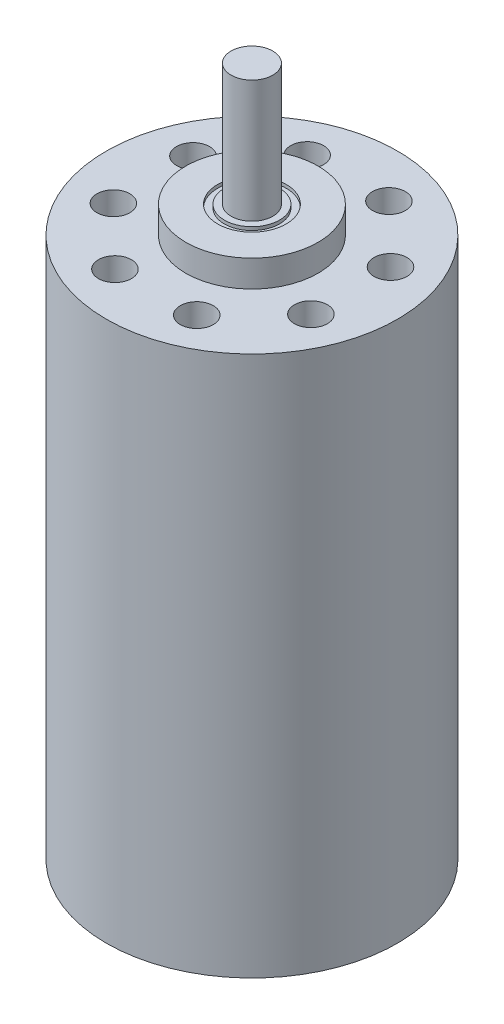
SolidWorks part; units mm, degrees
ref_plane "Front Plane" through (0, 0, 0) normal (0, 0, 1) x (1, 0, 0)
ref_plane "Top Plane" through (0, 0, 0) normal (0, 1, 0) x (1, 0, 0)
ref_plane "Right Plane" through (0, 0, 0) normal (1, 0, 0) x (0, 0, -1)
sketch "Sketch1" plane through (0, 0, 0) normal (0, 1, 0) x (1, 0, 0)
  circle A0 centre (0, 0) radius 11.049
  dimension "D1" = 22.098
extrude "Boss-Extrude1" add sketch "Sketch1" along normal blind 40.9956
sketch "Sketch2" plane through (0, 40.9956, 0) normal (0, 1, 0) x (1, 0, 0)
  circle A0 centre (0, 0) radius 5.0165
  dimension "D1" = 10.033
extrude "Boss-Extrude2" add sketch "Sketch2" along normal blind 2.032
sketch "Sketch3" plane through (0, 43.0276, 0) normal (0, 1, 0) x (1, 0, 0)
  circle A0 centre (0, 0) radius 1.585
  dimension "D1" = 3.17
extrude "Boss-Extrude3" add sketch "Sketch3" along normal blind 9.271
sketch "Sketch4" plane through (0, 52.2986, 0) normal (0, 1, 0) x (1, 0, 0)
  circle A0 centre (0, 0) radius 1.5939
  dimension "D1" = 3.1877
sketch "Sketch5" plane through (0, 40.9956, 0) normal (0, 1, 0) x (1, 0, 0)
  line L1 (-3.1626, 7.3483) -> (-7.4323, 2.9598) construction
  line L2 (-7.4323, 2.9598) -> (-7.3483, -3.1626) construction
  line L3 (-7.3483, -3.1626) -> (-2.9598, -7.4323) construction
  line L4 (-2.9598, -7.4323) -> (3.1626, -7.3483) construction
  line L5 (3.1626, -7.3483) -> (7.4323, -2.9598) construction
  line L6 (7.4323, -2.9598) -> (7.3483, 3.1626) construction
  line L7 (7.3483, 3.1626) -> (2.9598, 7.4323) construction
  line L8 (2.9598, 7.4323) -> (-3.1626, 7.3483) construction
  circle A0 centre (0, 0) radius 7.391 construction
  circle A1 centre (-7.4323, 2.9598) radius 1.25
  circle A2 centre (-3.1626, 7.3483) radius 1.25
  circle A3 centre (2.9598, 7.4323) radius 1.25
  circle A4 centre (7.3483, 3.1626) radius 1.25
  circle A5 centre (7.4323, -2.9598) radius 1.25
  circle A6 centre (3.1626, -7.3483) radius 1.25
  circle A7 centre (-2.9598, -7.4323) radius 1.25
  circle A8 centre (-7.3483, -3.1626) radius 1.25
  dimension "D2" = 2.5
  dimension "D1" = 16
sketch "Sketch6" plane through (0, 37.8206, 0) normal (0, 1, 0) x (1, 0, 0)
  circle A0 centre (0, 0) radius 10.6553
  circle A1 centre (0, 0) radius 11.049 construction
  dimension "D1" = 0.3937
extrude "Cut-Extrude4" cut sketch "Sketch5" against normal blind 3.175
sketch "Sketch7" plane through (0, 43.0276, 0) normal (0, 1, 0) x (1, 0, 0)
  circle A0 centre (0, 0) radius 2.601
  circle A1 centre (0, 0) radius 2.093
  circle A2 centre (0, 0) radius 1.585 construction
  dimension "D1" = 0.508
  dimension "D2" = 0.508
extrude "Cut-Extrude5" cut sketch "Sketch7" against normal blind 0.254
